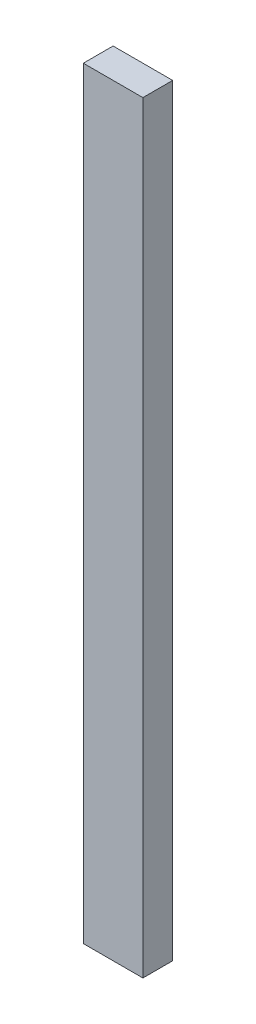
SolidWorks part; units mm, degrees
material "Plain Carbon Steel"
ref_plane "Front Plane" through (0, 0, 0) normal (0, 0, 1) x (1, 0, 0)
ref_plane "Top Plane" through (0, 0, 0) normal (0, 1, 0) x (1, 0, 0)
ref_plane "Right Plane" through (0, 0, 0) normal (1, 0, 0) x (0, 0, -1)
sketch "Sketch1" plane through (0, 0, 0) normal (0, 0, 1) x (1, 0, 0)
  line L0 (65, 0) -> (5, 0) construction
  line L1 (55, -4) -> (15, -4)
  line L2 (55, -4) -> (55, -516)
  line L3 (55, -516) -> (15, -516)
  line L4 (15, -4) -> (15, -516)
  line L5 (55, -4) -> (15, -516) construction
  line L6 (55, -516) -> (15, -4) construction
  point P0 (35, -260)
  dimension "D1" = 40
  dimension "D2" = 4
extrude "Boss-Extrude1" add sketch "Sketch1" along normal blind 20
sketch "Center_lines" plane through (0, 0, 0) normal (0, 0, -1) x (-1, 0, 0)
  line L0 (-35, -4) -> (-35, -516) construction
  line L1 (-55, -4) -> (-15, -4) construction
  line L2 (-15, -516) -> (-55, -516) construction
  line L3 (-55, -260) -> (-15, -260) construction
  line L4 (-55, -516) -> (-55, -4) construction
  line L5 (-15, -4) -> (-15, -516) construction
sketch "Center_lines_top" plane through (0, 0, 20) normal (0, 0, 1) x (1, 0, 0)
  line L0 (35, -4) -> (35, -516) construction
  line L1 (15, -260) -> (55, -260) construction
  point P8 (35, -260)
